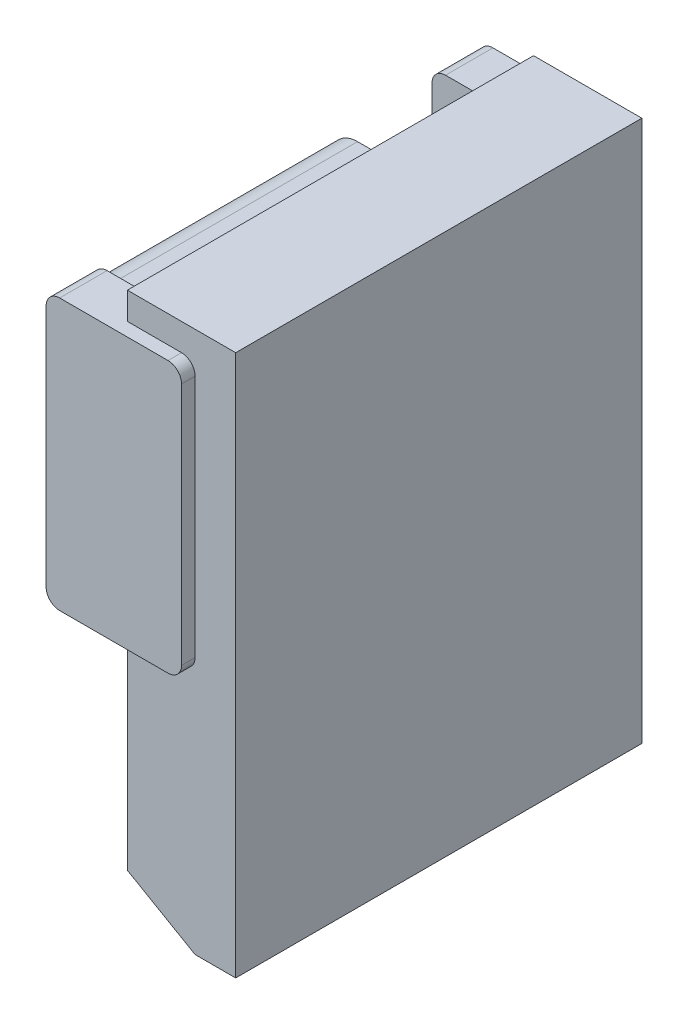
SolidWorks part; units mm, degrees
ref_plane "前视基准面" through (0, 0, 0) normal (0, 0, 1) x (1, 0, 0)
ref_plane "上视基准面" through (0, 0, 0) normal (0, 1, 0) x (1, 0, 0)
ref_plane "右视基准面" through (0, 0, 0) normal (1, 0, 0) x (0, 0, -1)
other "Configuration Table"
sketch "草图1" plane through (0, 0, 0) normal (0, 0, 1) x (1, 0, 0)
  line L0 (0, 0) -> (0, 40)
  line L1 (0, 40) -> (-8, 40)
  line L2 (-8, 40) -> (-8, 2.8868)
  line L3 (-8, 2.8868) -> (-3, 0)
  line L4 (-3, 0) -> (0, 0)
  dimension "D1" = 40
  dimension "D2" = 8
  dimension "D3" = 5
  dimension "D4" = 30
extrude "凸台-拉伸1" add sketch "草图1" along normal mid plane 30
sketch "草图7" plane through (-8, 0, 0) normal (-1, 0, 0) x (0, 0, 1)
  line L0 (0, 0) -> (0, 36.2891) construction
  line L1 (15, 0) -> (-15, 0) construction
  line L2 (-5, 18) -> (5, 18)
  line L3 (-5, 18) -> (-5, 6)
  line L4 (-5, 6) -> (5, 6)
  line L5 (5, 18) -> (5, 6)
  line L6 (-5, 18) -> (5, 6) construction
  line L7 (-5, 6) -> (5, 18) construction
  line L8 (-12, 10) -> (-8, 10)
  line L9 (-12, 10) -> (-12, 6)
  line L10 (-12, 6) -> (-8, 6)
  line L11 (-8, 10) -> (-8, 6)
  line L12 (-12, 10) -> (-8, 6) construction
  line L13 (-12, 6) -> (-8, 10) construction
  line L14 (12, 6) -> (8, 10) construction
  line L15 (12, 10) -> (8, 6) construction
  line L16 (8, 10) -> (8, 6)
  line L17 (12, 6) -> (8, 6)
  line L18 (12, 10) -> (12, 6)
  line L19 (12, 10) -> (8, 10)
  point P3 (0, 12)
  point P8 (-10, 8)
  point P19 (10, 8)
  dimension "D1" = 4
  dimension "D2" = 4
  dimension "D3" = 10
  dimension "D4" = 12
  dimension "D5" = 6
  dimension "D6" = 24
extrude "切除-拉伸1" cut sketch "草图7" against normal blind 1
sketch "草图9" plane through (0, 0, 0) normal (0, 0, 1) x (1, 0, 0)
  line L0 (-7, 12) -> (-23.7306, 12) construction
  line L2 (-7, 18) -> (-7, 6) construction
  line L3 (-7, 14) -> (-8, 14)
  line L4 (-8, 14) -> (-12, 13)
  line L6 (-12, 13) -> (-12, 11)
  line L7 (-8, 10) -> (-12, 11)
  line L8 (-7, 10) -> (-8, 10)
  line L9 (-3, 0) -> (0, 0) construction
  line L10 (-8, 40) -> (-8, 2.8868) construction
  line L11 (-7, 14) -> (-7, 10)
  point P9 (-12, 12)
  dimension "D1" = 2
  dimension "D2" = 4
  dimension "D3" = 10
  dimension "D4" = 4
extrude "凸台-拉伸2" add sketch "草图9" along normal mid plane 9
sketch "草图15" plane through (0, 0, 0) normal (0, 0, 1) x (1, 0, 0)
  line L0 (-8, 31) -> (-16, 31) construction
  line L1 (-8, 40) -> (-8, 2.8868) construction
  line L2 (-8, 29) -> (-16, 29)
  line L3 (-8, 33) -> (-16, 33)
  line L4 (-3, 0) -> (0, 0) construction
  arc A0 (-8, 29) -> (-8, 33) centre (-8, 31) ccw
  arc A1 (-16, 33) -> (-16, 29) centre (-16, 31) ccw
  point P4 (-12, 31)
  point P9 (0, 0)
  dimension "D1" = 10
  dimension "D2" = 2
  dimension "D3" = 29
extrude "凸台-拉伸3" add sketch "草图15" along normal mid plane 20
sketch "草图16" plane through (0, 0, 15) normal (0, 0, 1) x (1, 0, 0)
  line L0 (0, 0) -> (0, 40) construction
  line L1 (-4, 18) -> (-12, 18)
  line L2 (-3, 19) -> (-3, 37)
  line L3 (-4, 38) -> (-12, 38)
  line L4 (-13, 19) -> (-13, 37)
  line L5 (-3, 0) -> (0, 0) construction
  arc A0 (-12, 18) -> (-13, 19) centre (-12, 19) cw
  arc A1 (-12, 38) -> (-13, 37) centre (-12, 37) ccw
  arc A2 (-3, 37) -> (-4, 38) centre (-4, 37) ccw
  arc A3 (-4, 18) -> (-3, 19) centre (-4, 19) ccw
  point P10 (-13, 18)
  point P13 (-13, 38)
  point P16 (-3, 38)
  dimension "D5" = 1
  dimension "D6" = 1
  dimension "D1" = 10
  dimension "D2" = 3
  dimension "D3" = 20
  dimension "D4" = 18
extrude "凸台-拉伸4" add sketch "草图16" against normal blind 3.5 from offset 1
mirror "镜向1" about plane through (0, 0, 0) normal (0, 0, 1) of "凸台-拉伸4"
